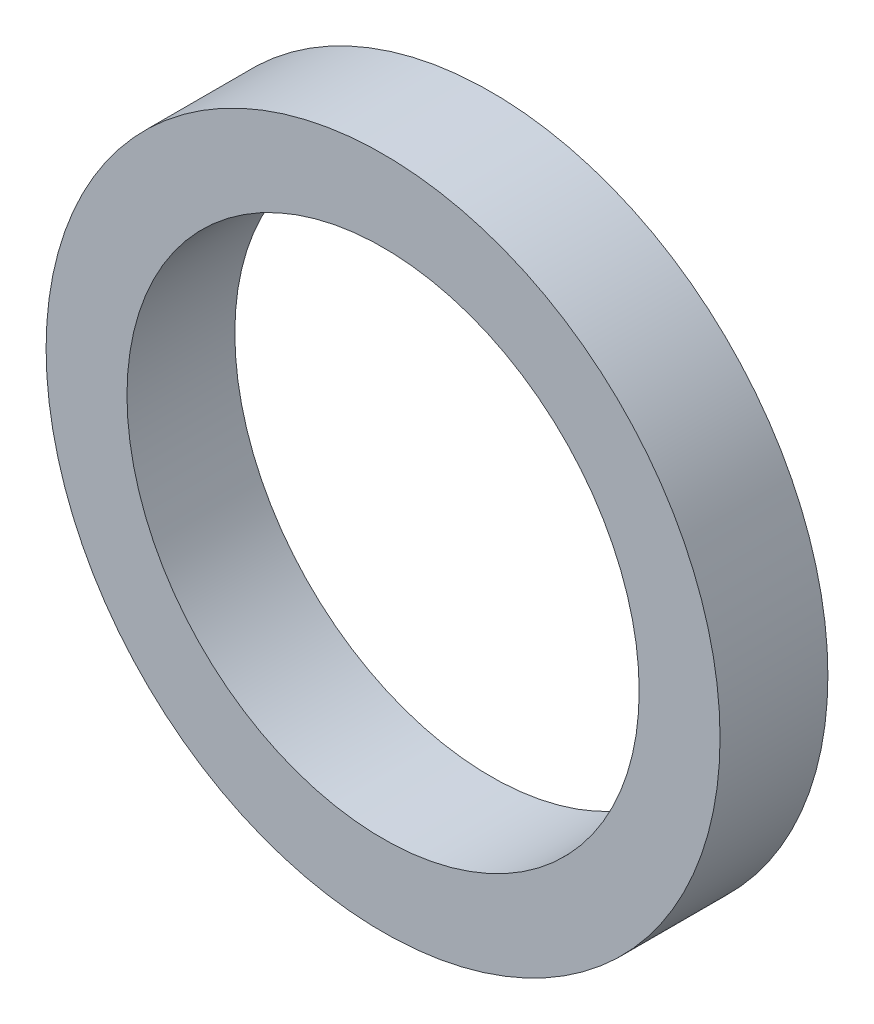
SolidWorks part; units mm, degrees
ref_plane "Front Plane" through (0, 0, 0) normal (0, 0, 1) x (1, 0, 0)
ref_plane "Top Plane" through (0, 0, 0) normal (0, 1, 0) x (1, 0, 0)
ref_plane "Right Plane" through (0, 0, 0) normal (1, 0, 0) x (0, 0, -1)
sketch "Sketch1" plane through (0, 0, 0) normal (0, 0, 1) x (1, 0, 0)
  circle A0 centre (0, 0) radius 25
  circle A1 centre (0, 0) radius 19
  dimension "D1" = 38
  dimension "D2" = 50
extrude "Boss-Extrude1" add sketch "Sketch1" along normal blind 8
